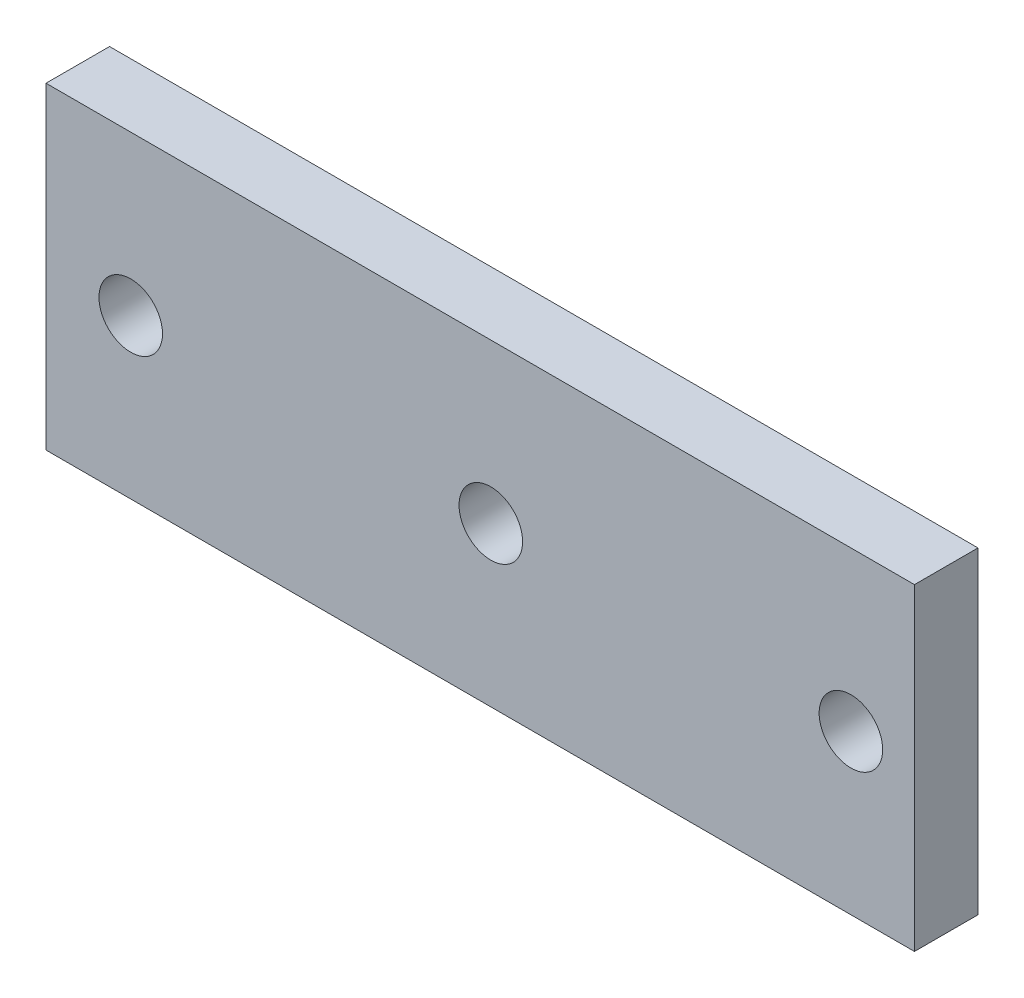
SolidWorks part; units mm, degrees
material "环氧树脂,未充填"
ref_plane "前视基准面" through (0, 0, 0) normal (0, 0, 1) x (1, 0, 0)
ref_plane "上视基准面" through (0, 0, 0) normal (0, 1, 0) x (1, 0, 0)
ref_plane "右视基准面" through (0, 0, 0) normal (1, 0, 0) x (0, 0, -1)
sketch "草图1" plane through (0, 0, 0) normal (0, 0, 1) x (1, 0, 0)
  line L1 (-20.5, -7.5) -> (20.5, -7.5)
  line L2 (-20.5, -7.5) -> (-20.5, 7.5)
  line L3 (-20.5, 7.5) -> (20.5, 7.5)
  line L4 (20.5, -7.5) -> (20.5, 7.5)
  line L5 (-20.5, -7.5) -> (20.5, 7.5) construction
  line L6 (-20.5, 7.5) -> (20.5, -7.5) construction
  point P0 (0, 0)
  dimension "D1" = 15
  dimension "D2" = 41
extrude "凸台-拉伸1" add sketch "草图1" along normal blind 3
sketch "草图2" plane through (0, 0, 3) normal (0, 0, 1) x (1, 0, 0)
  line L0 (-20.5, 0) -> (20.5, 0) construction
  line L1 (-20.5, 7.5) -> (-20.5, -7.5) construction
  line L2 (20.5, -7.5) -> (20.5, 7.5) construction
  circle A0 centre (-16.5, 0) radius 1.5
  circle A1 centre (0.5, 0) radius 1.5
  circle A2 centre (17.5, 0) radius 1.5
  dimension "D1" = 17
  dimension "D4" = 3
  dimension "D2" = 4
  dimension "D3" = 17
extrude "切除-拉伸1" cut sketch "草图2" against normal through all
